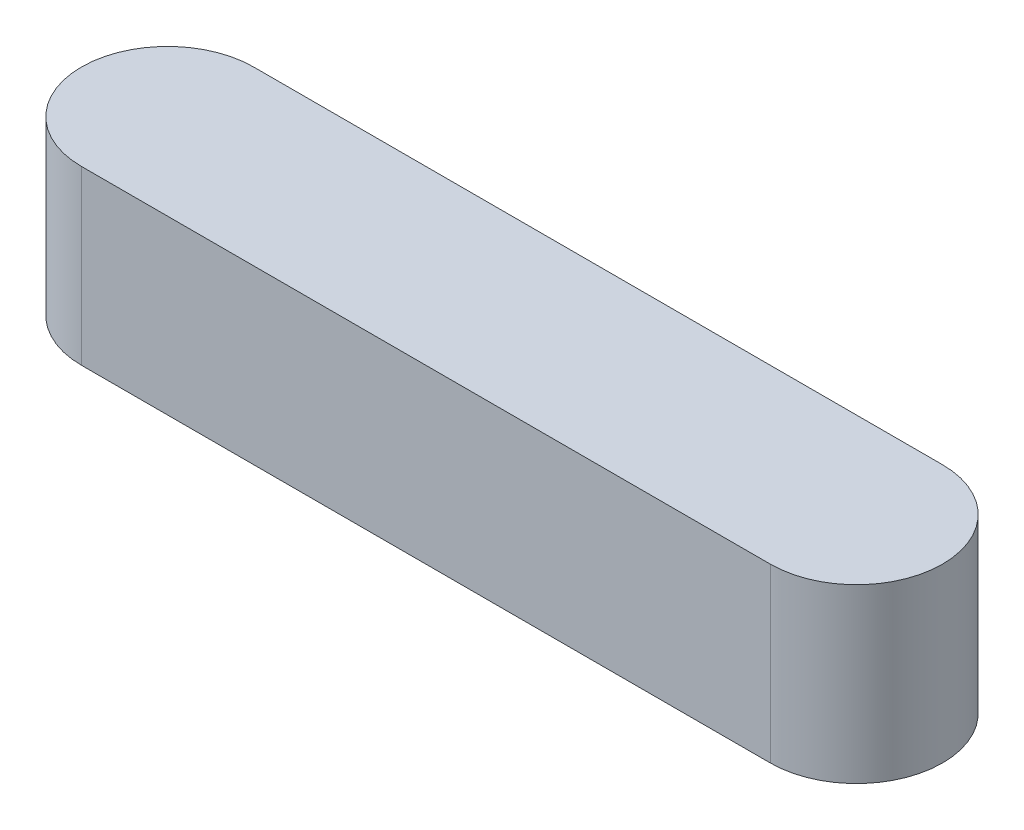
SolidWorks part; units mm, degrees
material "AISI 1045 钢，冷拔"
ref_plane "Front" through (0, 0, 0) normal (0, 0, 1) x (1, 0, 0)
ref_plane "Top" through (0, 0, 0) normal (0, 1, 0) x (1, 0, 0)
ref_plane "Right" through (0, 0, 0) normal (1, 0, 0) x (0, 0, -1)
sketch "草图1" plane through (0, 0, 0) normal (0, 1, 0) x (1, 0, 0)
  line L0 (-4, 0) -> (4, 0) construction
  line L1 (-4, 1) -> (4, 1)
  line L2 (-4, -1) -> (4, -1)
  line L3 (-5, -1) -> (-5, 1) construction
  line L4 (5, -1) -> (5, 1) construction
  line L5 (-5, 1) -> (5, 1) construction
  line L6 (-5, -1) -> (5, -1) construction
  arc A0 (-4, 1) -> (-4, -1) centre (-4, 0) ccw
  arc A1 (4, -1) -> (4, 1) centre (4, 0) ccw
  point P2 (0, 0)
  point P11 (-5, 0)
  point P14 (5, 0)
  dimension "b" = 1
  dimension "L" = 10
extrude "凸台-拉伸1" add sketch "草图1" along normal mid plane 2
other "冻结***"
